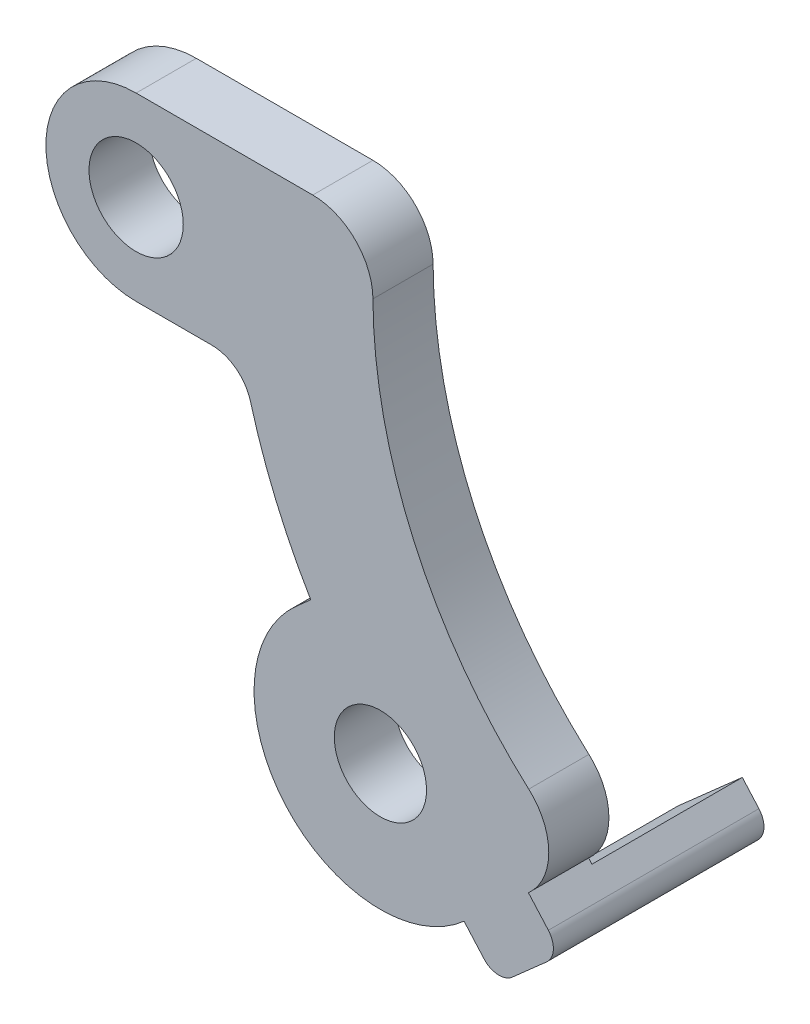
SolidWorks part; units mm, degrees
ref_plane "Front Plane" through (0, 0, 0) normal (0, 0, 1) x (1, 0, 0)
ref_plane "Top Plane" through (0, 0, 0) normal (0, 1, 0) x (1, 0, 0)
ref_plane "Right Plane" through (0, 0, 0) normal (1, 0, 0) x (0, 0, -1)
sketch "Sketch1" plane through (0, 0, -130.2439) normal (0, 0, 1) x (1, 0, 0)
  line L0 (-15.7081, 37.5725) -> (-15.0101, 38.1894) construction
  line L6 (-15.7081, 37.5725) -> (-15.0101, 38.1894)
  line L21 (1.2909, 35.7798) -> (-7.3644, 28.1309) construction
  line L22 (-17.5363, 52.8349) -> (-17.5363, 78.2517)
  line L23 (-1.1666, 35.6099) -> (-8.3577, 29.2549)
  line L26 (-14.7148, 36.4485) -> (-13.0642, 37.9072)
  line L31 (-4.1549, 30.9672) -> (-7.3644, 28.1309)
  line L35 (-23.7161, 46.719) -> (-19.9422, 46.719)
  line L36 (-23.7161, 55.719) -> (-14.9089, 55.719)
  arc A21 (-11.5363, 35.1017) -> (-11.5363, 30.6017) centre (-11.5363, 32.8517) ccw construction
  arc A22 (30.9499, 61.6319) -> (-1.1666, 35.6099) centre (11.4637, 52.8517) ccw
  arc A23 (-17.5363, 52.8349) -> (-13.0642, 37.9072) centre (9.6137, 52.8349) ccw
  arc A24 (-14.7148, 36.4485) -> (-8.3577, 29.2549) centre (-11.5363, 32.8517) ccw
  arc A25 (-9.8393, 51.1233) -> (-0.3376, 35.0322) centre (11.4637, 52.8517) ccw
  arc A28 (-11.5363, 30.6017) -> (-11.5363, 35.1017) centre (-11.5363, 32.8517) ccw construction
  arc A29 (-11.5363, 35.1017) -> (-11.5363, 30.6017) centre (-11.5363, 32.8517) ccw
  arc A30 (-11.5363, 30.6017) -> (-11.5363, 35.1017) centre (-11.5363, 32.8517) ccw
  arc A31 (-15.7081, 37.5725) -> (-7.3644, 28.1309) centre (-11.5363, 32.8517) ccw construction
  arc A32 (-19.9422, 46.719) -> (-18.0136, 45.2485) centre (-19.9422, 44.719) cw
  arc A33 (-15.7081, 37.5725) -> (-7.3644, 28.1309) centre (-11.5363, 32.8517) ccw
  circle A35 centre (-23.7161, 51.219) radius 2.25
  arc A36 (-23.7161, 55.719) -> (-23.7161, 46.719) centre (-23.7161, 51.219) ccw
  arc A40 (-11.909, 52.7341) -> (-4.1388, 35.4489) centre (11.4637, 52.8517) ccw
  arc A41 (-18.0136, 45.2485) -> (-15.0101, 38.1894) centre (9.6137, 52.8349) ccw
  arc A42 (-19.0363, 52.8517) -> (-15.0101, 38.1894) centre (9.6137, 52.8349) ccw construction
  arc A43 (-11.8327, 50.9616) -> (-1.4419, 33.3648) centre (11.4637, 52.8517) ccw construction
  arc A44 (-4.1388, 35.4489) -> (-4.1549, 30.9672) centre (-6.1415, 33.2152) cw
  arc A45 (-11.909, 52.7341) -> (-14.9089, 55.719) centre (-14.9089, 52.719) ccw
  circle A46 centre (-23.7161, 51.219) radius 2.35
  circle A47 centre (-11.5363, 32.8517) radius 2.3
  point P25 (-9.7161, 55.719)
  line M29 (-19.0363, 78.2517) -> (-19.0363, 52.8517)
  arc M30 (-19.0363, 52.8517) -> (-15.0101, 38.1894) centre (9.6137, 52.8349) ccw
  line M31 (-15.0101, 38.1894) -> (-15.7081, 37.5725)
  arc M32 (-15.7081, 37.5725) -> (-7.3644, 28.1309) centre (-11.5363, 32.8517) ccw
  line M33 (-7.3644, 28.1309) -> (1.2909, 35.7798)
  circle M35 centre (-11.5363, 32.8517) radius 2.25
  dimension "D1" = 1.5
  dimension "D2" = 2
  dimension "D3" = 3
  dimension "D4" = 2
  dimension "D5" = 4.5
  dimension "D6" = 14
  dimension "D7" = 4.7
  dimension "D8" = 4.6
extrude "Boss-Extrude2" add sketch "Sketch1" along normal blind 3 contours L36 A36 L35 A32 A35 M30 M29 | A40 A45 L36 A44 M29 M30 M31 M32 M33 M35
sketch "Sketch2" plane through (-17.188, 19.4496, 0) normal (0.6622, -0.7493, 0) x (0.7493, 0.6622, 0)
  line L4 (13.1099, -130.2439) -> (17.3931, -130.2439)
  line L5 (17.3931, -130.2439) -> (17.3931, -127.2439)
  line L6 (17.3931, -127.2439) -> (13.1099, -127.2439)
  line L7 (13.1099, -127.2439) -> (13.1099, -130.2439)
  line L8 (13.1099, -130.2439) -> (17.3931, -130.2439)
  line L9 (17.3931, -130.2439) -> (17.3931, -127.2439)
  line L10 (17.3931, -127.2439) -> (13.1099, -127.2439)
  line L11 (13.1099, -127.2439) -> (13.1099, -130.2439)
  dimension "D1" = 0
extrude "Boss-Extrude3" add sketch "Sketch2" along normal blind 2.5
sketch "Sketch3" plane through (0, 0, -127.2439) normal (0, 0, 1) x (1, 0, 0)
  line L0 (-7.3644, 28.1309) -> (-4.1549, 30.9672)
  line L1 (-4.1549, 30.9672) -> (-2.4994, 29.0939)
  line L2 (-2.4994, 29.0939) -> (-5.7089, 26.2576)
  line L3 (-5.7089, 26.2576) -> (-7.3644, 28.1309)
extrude "Boss-Extrude4" add sketch "Sketch3" against normal blind 10.5
fillet "Fillet1" radius 1 2 edges at (-5.7089, 26.2576, -132.4939) (-2.4994, 29.0939, -132.4939)
sketch "Sketch4" plane through (-17.188, 19.4496, 0) normal (-0.6622, 0.7493, 0) x (0.7493, 0.6622, 0)
  line L4 (13.1099, 130.2439) -> (17.3931, 130.2439)
  line L5 (13.1099, 137.7439) -> (13.1099, 130.2439)
  line L6 (17.3931, 137.7439) -> (13.1099, 137.7439)
  line L7 (17.3931, 130.2439) -> (17.3931, 137.7439)
  line L9 (13.1099, 137.7439) -> (13.1099, 130.2439)
  line L10 (17.3931, 137.7439) -> (13.1099, 137.7439)
  line L11 (17.3931, 130.2439) -> (17.3931, 137.7439)
  line L12 (13.1099, 130.2439) -> (17.3931, 130.2439)
  dimension "D1" = 0
extrude "Cut-Extrude1" cut sketch "Sketch4" against normal blind 0.25
